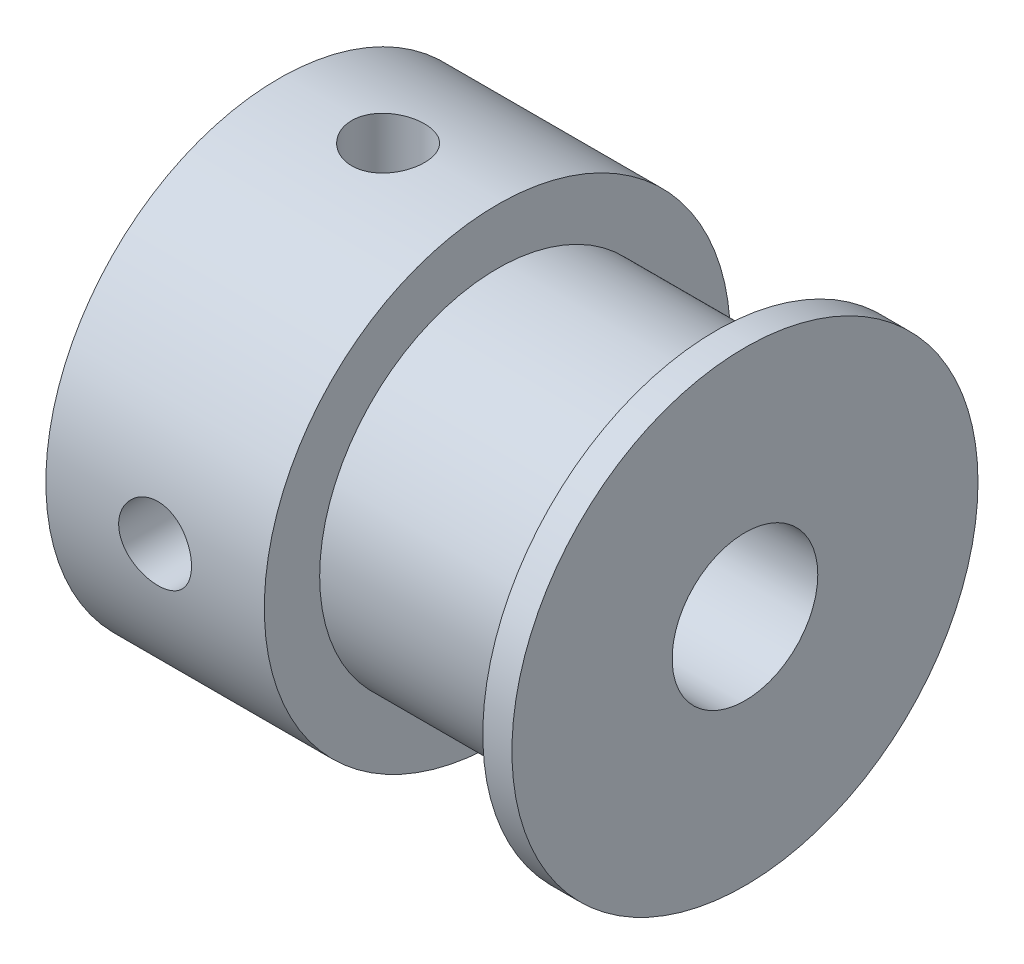
SolidWorks part; units mm, degrees
material "6061-T6 (SS)"
ref_plane "Front Plane" through (0, 0, 0) normal (0, 0, 1) x (1, 0, 0)
ref_plane "Top Plane" through (0, 0, 0) normal (0, 1, 0) x (1, 0, 0)
ref_plane "Right Plane" through (0, 0, 0) normal (1, 0, 0) x (0, 0, -1)
sketch "Sketch1" plane through (0, 0, 0) normal (0, 0, 1) x (1, 0, 0)
  line L0 (0, 2.5) -> (0, 8)
  line L1 (0, 8) -> (7.5, 8)
  line L2 (7.5, 8) -> (7.5, 6.1)
  line L3 (7.5, 6.1) -> (15, 6.1)
  line L4 (15, 6.1) -> (15, 8)
  line L5 (15, 8) -> (16, 8)
  line L6 (16, 8) -> (16, 2.5)
  line L7 (16, 2.5) -> (0, 2.5)
  line L8 (0, 0) -> (-7.6744, 0) construction
  dimension "D1" = 5
  dimension "D2" = 16
  dimension "D3" = 12.2
  dimension "D4" = 7.5
  dimension "D5" = 16
  dimension "D6" = 1
revolve "Revolve1" add sketch "Sketch1" angle 360 about L8
hole_wizard "M3x0.5 Tapped Hole1" positions "Sketch3" profile "Sketch2" tap size "M3x0.5" standard "ANSI Metric"
sketch "Sketch3" plane through (0, 0, 0) normal (0, 1, 0) x (1, 0, 0)
  line L0 (0, 0) -> (7.5, 0) construction
  line L1 (7.5, -6.1) -> (7.5, 6.1) construction
  point P8 (3.75, 0)
sketch "Sketch2" plane through (3.75, 0, 0) normal (1, 0, 0) x (0, 0, -1)
  line L0 (0, 0) -> (0, 8)
  line L1 (0, 8) -> (1.25, 8)
  line L2 (1.25, 8) -> (1.25, 0)
  line L5 (1.25, 0) -> (0, 0)
  line L11 (0, -6.35) -> (0, 107.95) construction
  dimension "Thread Major Dia." = 2.5
  dimension "Thru Tap Drill Depth" = 8
hole_wizard "M3x0.5 Tapped Hole2" positions "Sketch5" profile "Sketch4" tap size "M3x0.5" standard "ANSI Metric"
sketch "Sketch5" plane through (0, 0, 0) normal (0, 0, 1) x (1, 0, 0)
  line L0 (0, 0) -> (7.5, 0) construction
  line L1 (7.5, -6.1) -> (7.5, 6.1) construction
  point P7 (3.75, 0)
sketch "Sketch4" plane through (3.75, 0, 0) normal (1, 0, 0) x (0, 1, 0)
  line L0 (0, 0) -> (0, 8)
  line L1 (0, 8) -> (1.25, 8)
  line L2 (1.25, 8) -> (1.25, 0)
  line L5 (1.25, 0) -> (0, 0)
  line L11 (0, -6.35) -> (0, 107.95) construction
  dimension "Thread Major Dia." = 2.5
  dimension "Thru Tap Drill Depth" = 8
